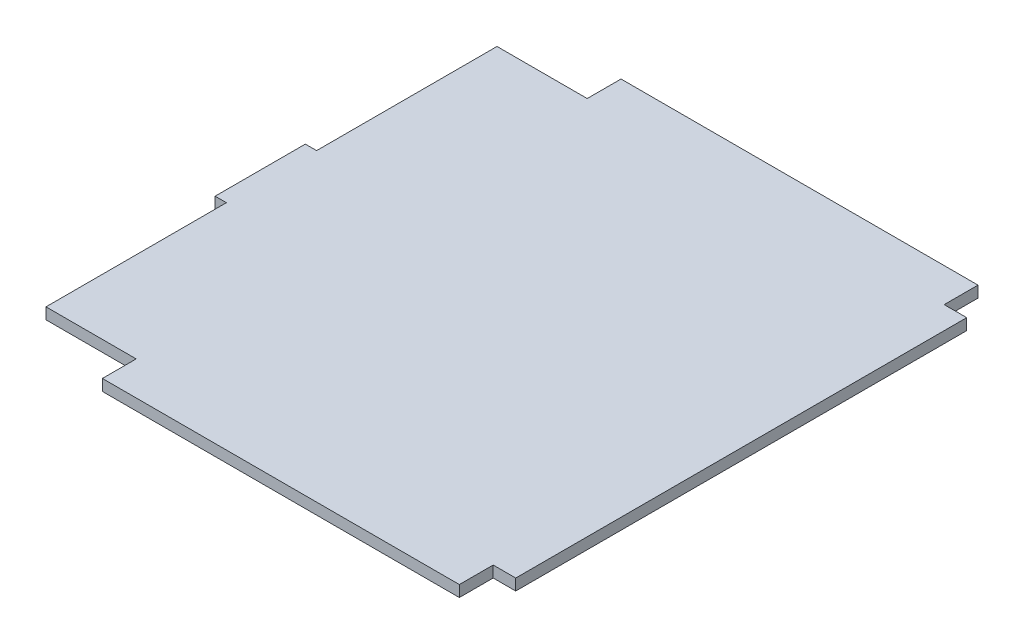
SolidWorks part; units mm, degrees
material "Acrylic (Medium-high impact)"
ref_plane "Front Plane" through (0, 0, 0) normal (0, 0, 1) x (1, 0, 0)
ref_plane "Top Plane" through (0, 0, 0) normal (0, 1, 0) x (1, 0, 0)
ref_plane "Right Plane" through (0, 0, 0) normal (1, 0, 0) x (0, 0, -1)
sketch "Sketch1" plane through (0, 0, 0) normal (0, 1, 0) x (1, 0, 0)
  line L0 (-66.1363, 66.4972) -> (66.1363, 66.4972) construction
  line L1 (66.1363, -73.025) -> (-66.1363, -73.025)
  line L2 (66.1363, -73.025) -> (66.1363, 73.025)
  line L3 (66.1363, 73.025) -> (-66.1363, 73.025)
  line L4 (-66.1363, -73.025) -> (-66.1363, 73.025)
  line L5 (66.1363, -73.025) -> (-66.1363, 73.025) construction
  line L6 (66.1363, 73.025) -> (-66.1363, -73.025) construction
  line L7 (-66.1363, -66.4972) -> (66.1363, -66.4972) construction
  line L8 (-66.1363, 66.4972) -> (-66.1363, -66.4972) construction
  line L9 (66.1363, 66.4972) -> (66.1363, -66.4972) construction
  line L19 (-66.1363, -12.7) -> (-69.3113, -12.7)
  line L20 (-66.1363, -73.025) -> (-40.7363, -73.025)
  line L21 (-66.1363, -73.025) -> (-66.1363, -63.5)
  line L22 (-66.1363, -63.5) -> (-40.7363, -63.5)
  line L23 (-40.7363, -73.025) -> (-40.7363, -63.5)
  line L24 (-66.1363, 73.025) -> (-40.7363, 73.025)
  line L25 (-66.1363, 73.025) -> (-66.1363, 63.5)
  line L26 (-66.1363, 63.5) -> (-40.7363, 63.5)
  line L27 (-40.7363, 73.025) -> (-40.7363, 63.5)
  line L28 (-66.1363, -12.7) -> (-66.1363, 12.7)
  line L29 (-66.1363, 12.7) -> (-69.3113, 12.7)
  line L30 (-69.3113, -12.7) -> (-69.3113, 12.7)
  line L31 (66.1363, 73.025) -> (59.7863, 73.025)
  line L32 (66.1363, 73.025) -> (66.1363, 63.5)
  line L33 (66.1363, 63.5) -> (59.7863, 63.5)
  line L34 (59.7863, 73.025) -> (59.7863, 63.5)
  line L35 (66.1363, -73.025) -> (59.7863, -73.025)
  line L36 (66.1363, -73.025) -> (66.1363, -63.5)
  line L37 (66.1363, -63.5) -> (59.7863, -63.5)
  line L38 (59.7863, -73.025) -> (59.7863, -63.5)
  point P0 (0, 0)
  point P10 (66.1363, 0)
  point P11 (66.1363, 0)
  point P16 (-69.3113, 0)
  dimension "D1" = 132.2725
  dimension "D2" = 146.05
  dimension "D3" = 132.9944
  dimension "D4" = 127
  dimension "D5" = 25.4
  dimension "D6" = 25.4
  dimension "D8" = 6.35
  dimension "D7" = 3.175
extrude "Boss-Extrude1" add sketch "Sketch1" along normal blind 3.175 contours L3 L27 L26 L4 L22 L23 L1 L2 | L30 L19 L4 L29
sketch "Sketch2" plane through (0, 0, 0) normal (0, -1, 0) x (1, 0, 0)
  line L0 (59.7863, -73.025) -> (-40.7363, -73.025) construction
  line L1 (31.2113, -73.025) -> (66.1363, -73.025)
  line L2 (31.2113, -73.025) -> (31.2113, 73.025)
  line L3 (31.2113, 73.025) -> (66.1363, 73.025)
  line L4 (66.1363, -73.025) -> (66.1363, 73.025)
  line L5 (59.7863, 73.025) -> (-40.7363, 73.025) construction
  line L6 (66.1363, 63.5) -> (66.1363, -63.5) construction
  line L7 (59.7863, -73.025) -> (59.7863, -63.5) construction
  dimension "D1" = 28.575
extrude "Cut-Extrude1" [suppressed] cut sketch "Sketch2" against normal through all
equation "\"wallThickness\"= .125in"
equation "\"D1@Boss-Extrude1\"=\"WallThickness\""
equation "\"D7@Sketch1\"=\"WallThickness\""
equation "\"bottomThickness\"= .25"
equation "\"chamberHeight\"= 15"
